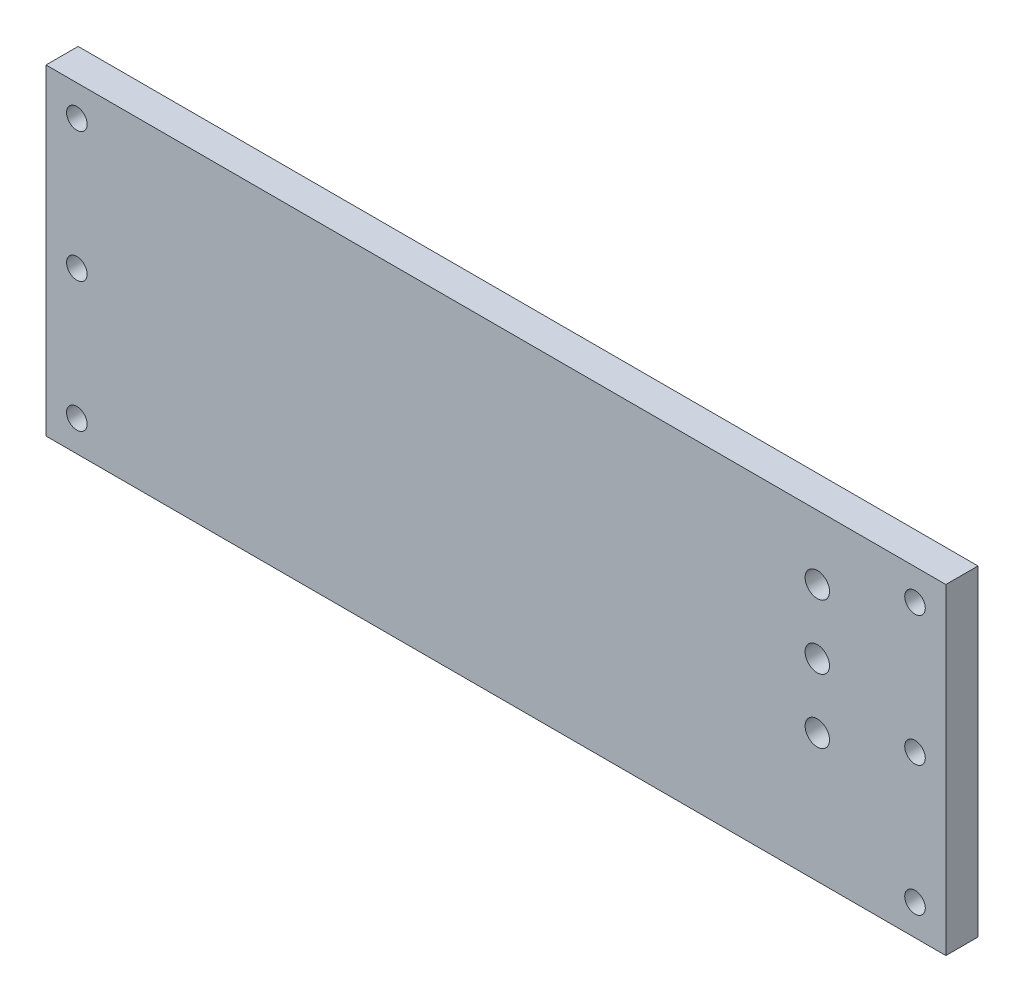
SolidWorks part; units mm, degrees
ref_plane "Front Plane" through (0, 0, 0) normal (0, 0, 1) x (1, 0, 0)
ref_plane "Top Plane" through (0, 0, 0) normal (0, 1, 0) x (1, 0, 0)
ref_plane "Right Plane" through (0, 0, 0) normal (1, 0, 0) x (0, 0, -1)
sketch "Sketch1" plane through (0, 0, 0) normal (0, 0, 1) x (1, 0, 0)
  line L0 (0, 0) -> (0, 6.176)
  line L1 (-88.9, -31.75) -> (88.9, -31.75)
  line L2 (-88.9, -31.75) -> (-88.9, 31.75)
  line L3 (-88.9, 31.75) -> (88.9, 31.75)
  line L4 (88.9, -31.75) -> (88.9, 31.75)
  line L5 (-88.9, -31.75) -> (88.9, 31.75) construction
  line L6 (-88.9, 31.75) -> (88.9, -31.75) construction
  circle A0 centre (-82.804, 25.654) radius 2.032
  circle A1 centre (-82.804, 0) radius 2.032
  circle A2 centre (-82.804, -25.654) radius 2.032
  circle A3 centre (82.804, -25.654) radius 2.032
  circle A4 centre (82.804, 0) radius 2.032
  circle A5 centre (82.804, 25.654) radius 2.032
  point P0 (0, 0)
  dimension "D3" = 4.064
  dimension "D1" = 177.8
  dimension "D2" = 63.5
  dimension "D4" = 6.096
  dimension "D5" = 6.096
  dimension "D6" = 3
extrude "Boss-Extrude1" add sketch "Sketch1" along normal blind 6.35
sketch "Sketch2" plane through (0, 0, 6.35) normal (0, 0, 1) x (1, 0, 0)
  line L0 (88.9, -31.75) -> (88.9, 31.75) construction
  line L1 (-88.9, 31.75) -> (88.9, 31.75) construction
  circle A0 centre (63.5, 19.05) radius 2.413
  dimension "D1" = 4.826
  dimension "D2" = 25.4
  dimension "D3" = 12.7
extrude "Cut-Extrude1" cut sketch "Sketch2" against normal blind 6.35
pattern_linear "LPattern1" count 3 spacing 12.7 along (0, -1, 0) of "Cut-Extrude1"
